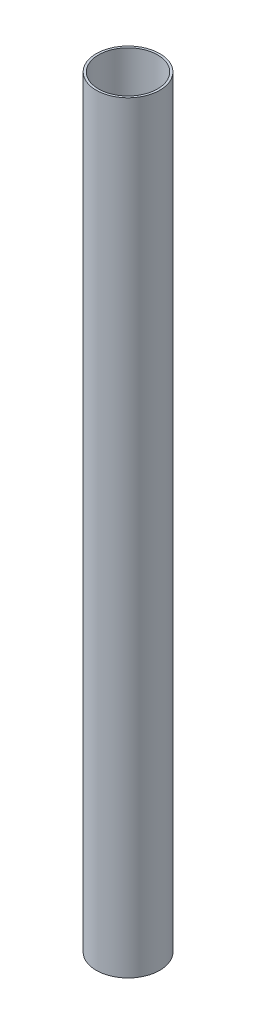
SolidWorks part; units mm, degrees
material "6061 Alloy"
ref_plane "Front Plane" through (0, 0, 0) normal (0, 0, 1) x (1, 0, 0)
ref_plane "Top Plane" through (0, 0, 0) normal (0, 1, 0) x (1, 0, 0)
ref_plane "Right Plane" through (0, 0, 0) normal (1, 0, 0) x (0, 0, -1)
sketch "Sketch1" plane through (0, 0, 0) normal (0, 1, 0) x (1, 0, 0)
  circle A0 centre (0, 0) radius 12.7
  circle A1 centre (0, 0) radius 11.811
  dimension "D1" = 25.4
  dimension "D2" = 0.889
extrude "Boss-Extrude1" add sketch "Sketch1" along normal mid plane 304.8
